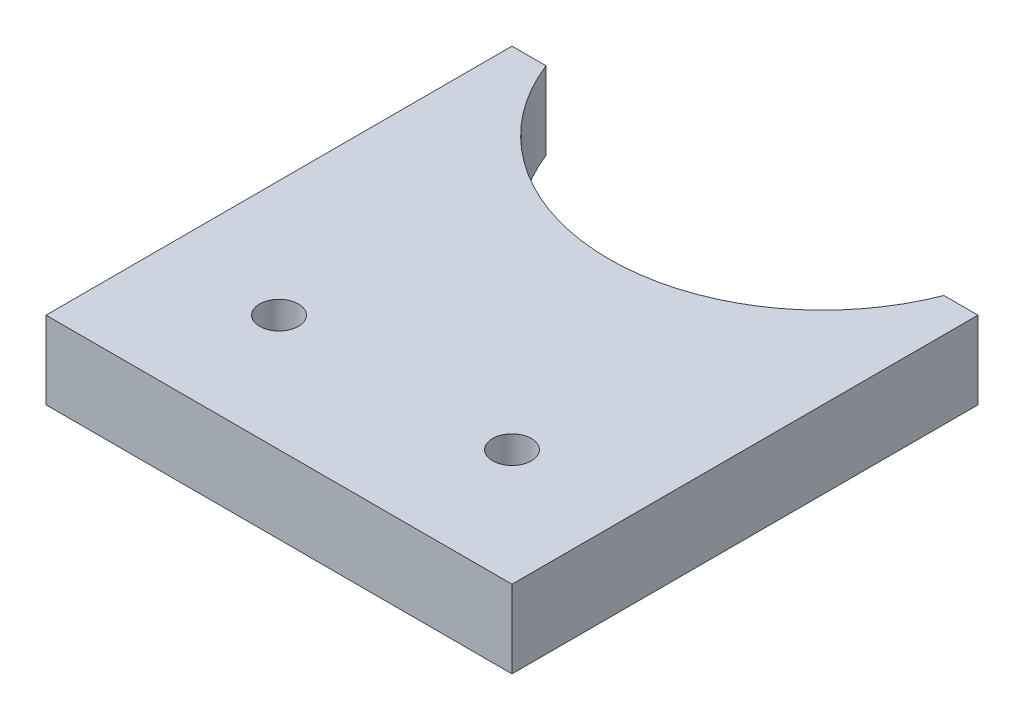
SolidWorks part; units mm, degrees
ref_plane "Front Plane" through (0, 0, 0) normal (0, 0, 1) x (1, 0, 0)
ref_plane "Top Plane" through (0, 0, 0) normal (0, 1, 0) x (1, 0, 0)
ref_plane "Right Plane" through (0, 0, 0) normal (1, 0, 0) x (0, 0, -1)
sketch "Sketch1" plane through (0, 0, 0) normal (0, 1, 0) x (1, 0, 0)
  line L0 (0, -66.5769) -> (0, 65.2745) construction
  line L1 (-39.8557, 0) -> (45.6204, 0) construction
  line L2 (38.1, 38.1) -> (32.5341, 38.1)
  line L3 (-38.1, 38.1) -> (-38.1, -38.1)
  line L4 (38.1, 38.1) -> (38.1, -38.1)
  line L5 (38.1, -38.1) -> (-38.1, -38.1)
  line L6 (-32.5341, 38.1) -> (-38.1, 38.1)
  arc A0 (-32.5341, 38.1) -> (32.5341, 38.1) centre (0, 50.8) ccw
  point P10 (0, 38.1)
  point P11 (38.1, 0)
  point P12 (-38.1, 0)
  dimension "D1" = 76.2
  dimension "D3" = 69.85
  dimension "D2" = 76.2
  dimension "D4" = 12.7
extrude "Boss-Extrude1" add sketch "Sketch1" along normal blind 12.7
sketch "Sketch2" plane through (0, 12.7, 0) normal (0, 1, 0) x (1, 0, 0)
  line L0 (-38.1, -19.05) -> (38.1, -19.05) construction
  line L1 (-38.1, 38.1) -> (-38.1, -38.1) construction
  line L2 (38.1, -38.1) -> (38.1, 38.1) construction
  line L3 (0, -38.1) -> (0, -4.7889) construction
  line L4 (-38.1, -38.1) -> (38.1, -38.1) construction
  circle A0 centre (-19.05, -19.05) radius 3.175
  circle A1 centre (19.05, -19.05) radius 3.175
  dimension "D1" = 6.35
  dimension "D2" = 38.1
  dimension "D3" = 19.05
extrude "Cut-Extrude1" cut sketch "Sketch2" against normal blind 12.7
